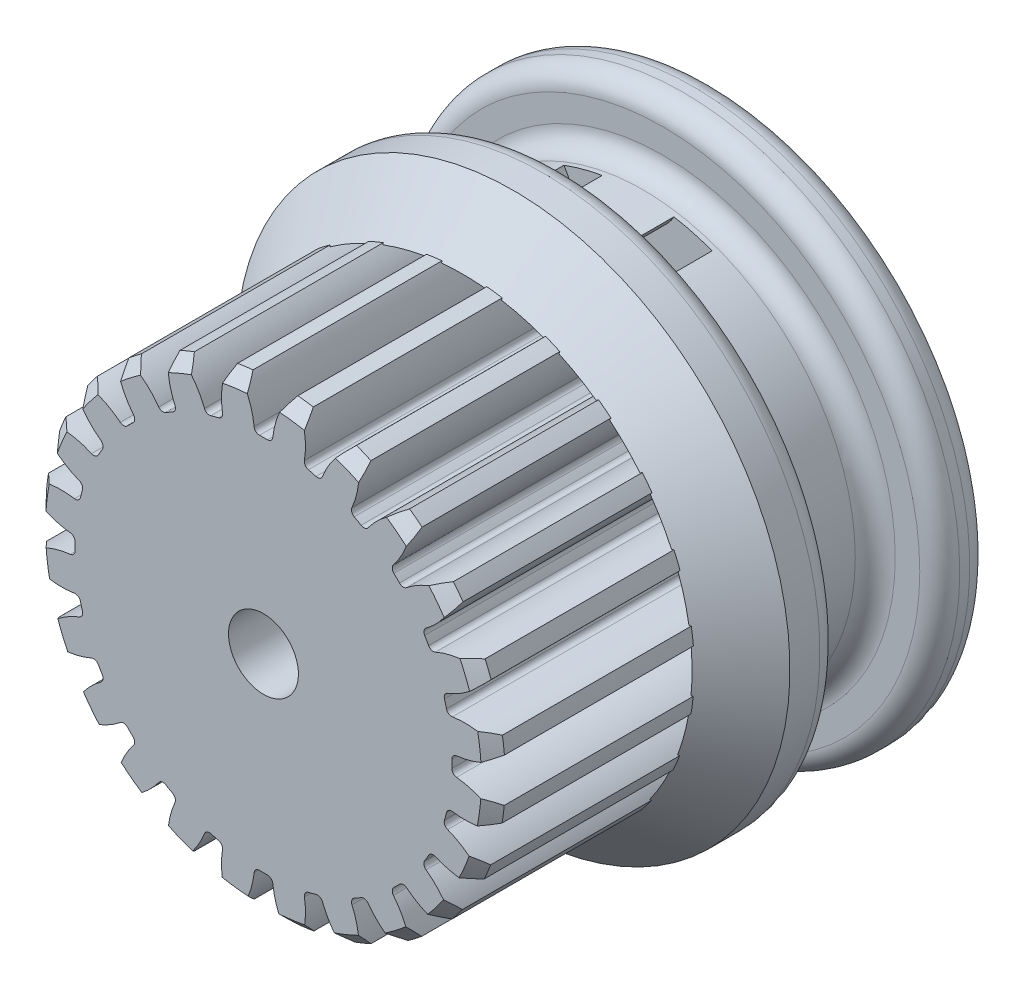
SolidWorks part; units mm, degrees
ref_plane "Plan de face" through (0, 0, 0) normal (0, 0, 1) x (1, 0, 0)
ref_plane "Plan de dessus" through (0, 0, 0) normal (0, 1, 0) x (1, 0, 0)
ref_plane "Plan de droite" through (0, 0, 0) normal (1, 0, 0) x (0, 0, -1)
sketch "Sketch1" plane through (0, 0, 0) normal (0, 0, 1) x (1, 0, 0)
  circle A0 centre (0, 0) radius 21.25 construction
  circle A1 centre (0, 0) radius 23.0208
  dimension "D1" = 42.5
  dimension "D2" = 46.0417
extrude "Boss-Extrude1" add sketch "Sketch1" along normal mid plane 25
sketch "Sketch2" plane through (0, 0, 12.5) normal (0, 0, 1) x (1, 0, 0)
  line L0 (0, 23.0208) -> (0, 0) construction
  line L1 (0, 0) -> (5.9582, 22.2364) construction
  line L2 (0, 0) -> (3.0048, 22.8239) construction
  line L3 (-0.8962, 18.7494) -> (0, 0) construction
  line L4 (-1.3898, 21.2045) -> (1.3898, 21.2045) construction
  line L5 (1.3898, 21.2045) -> (4.1457, 20.8417) construction
  line L6 (-2.0186, 22.9322) -> (0, 17.386) construction
  arc A0 (0.8962, 18.7494) -> (-0.8962, 18.7494) centre (0, 0) ccw
  circle A1 centre (0, 0) radius 19.4792 construction
  circle A2 centre (0, 0) radius 23.0208 construction
  arc A3 (2.2433, 22.9113) -> (0.8962, 18.7494) centre (9.2295, 18.3511) ccw
  arc A4 (-2.2433, 22.9113) -> (-0.8962, 18.7494) centre (-9.2295, 18.3511) cw
  circle A5 centre (0, 0) radius 23.0208 construction
  circle A6 centre (0, 0) radius 21.25 construction
  arc A7 (-2.2433, 22.9113) -> (2.2433, 22.9113) centre (0, 0) cw
  dimension "D1" = 15
  dimension "D2" = 3.5417
  dimension "D3" = 4.25
  dimension "D4" = 20
extrude "Cut-Extrude1" cut sketch "Sketch2" against normal through all
fillet "Fillet1" radius 0.5312 2 edges at (0.8962, 18.7494, 0) (-0.8962, 18.7494, 0)
chamfer "Chamfer1" distance 1.2 1 edges at (0, -23.0208, 12.5)
pattern_circular "CirPattern2" count 24 over 360 about axis through (0, -0.0957, 0) along (0, 0, 1) of "Fillet1", "Cut-Extrude1"
sketch "Sketch4" plane through (0, 0, 0) normal (1, 0, 0) x (0, 0, -1)
  line L2 (12.5, 27.707) -> (17.5, 27.707)
  line L3 (17.5, 27.707) -> (17.5, 21.25)
  line L4 (17.5, 21.25) -> (27.5, 21.25)
  line L5 (27.5, 21.25) -> (27.5, 27.707)
  line L6 (27.5, 27.707) -> (32.5, 27.707)
  line L7 (32.5, 27.707) -> (32.5, 0)
  line L8 (32.5, 0) -> (12.5, 0)
  line L9 (12.5, 0) -> (12.5, 22.9113)
  line L10 (12.5, 22.9113) -> (7.5, 22.9113)
  line L11 (12.5, 22.707) -> (-11.3, 22.707) construction
  line L12 (12.5, 22.9113) -> (-11.3, 22.9113) construction
  line L13 (7.5, 22.9113) -> (12.5, 27.707)
  dimension "D1" = 20
  dimension "D2" = 5
  dimension "D3" = 5
  dimension "D4" = 21.25
  dimension "D5" = 5
  dimension "D6" = 5
  dimension "D7" = 10
revolve "Revolve1" add sketch "Sketch4" angle 360 about L8
fillet "Fillet2" radius 2 5 edges at (-27.707, 0, -17.5) (-21.25, 0, -17.5) (-21.25, 0, -27.5) (-27.707, 0, -27.5) (-27.707, 0, -32.5)
sketch "Sketch5" plane through (0, 0, -32.5) normal (0, 0, -1) x (-1, 0, 0)
  circle A0 centre (0, 0) radius 7
  dimension "D1" = 14
extrude "Boss-Extrude3" add sketch "Sketch5" along normal blind 10
sketch "Sketch6" plane through (0, 0, -42.5) normal (0, 0, -1) x (-1, 0, 0)
  circle A0 centre (0, 0) radius 3.5
  dimension "D1" = 7
extrude "Cut-Extrude2" cut sketch "Sketch6" against normal through all
sketch "Sketch7" plane through (0, 0, 0) normal (1, 0, 0) x (0, 0, -1)
  line L0 (32.5, 0) -> (42.5, 0) construction
  line L1 (32.5, -7) -> (32.5, 7) construction
  line L2 (42.5, -7) -> (42.5, 7) construction
  circle A1 centre (37.5, 0) radius 1.725
  point P8 (0, 0)
  point P9 (37.5, 0)
  dimension "D1" = 3.45
extrude "Cut-Extrude3" cut sketch "Sketch7" against normal blind 10
sketch "Sketch8" plane through (0, 0, 0) normal (0, 0, 1) x (1, 0, 0)
  line L0 (0, 0) -> (0, 27.707) construction
  circle A0 centre (0, 0) radius 21.25 construction
  arc A1 (-7.4207, 19.9122) -> (-3.5898, 20.9446) centre (0, 0) cw
  arc A2 (-7.4207, 19.9122) -> (7.4207, 19.9122) centre (0, 23.5764) ccw
  arc A3 (7.4207, 19.9122) -> (3.5898, 20.9446) centre (0, 0) ccw
  arc A4 (3.5898, 20.9446) -> (-3.5898, 20.9446) centre (0, 22.8372) cw
  point P10 (0, 18.779)
  point P14 (0, 15.3003)
  point P15 (0, 0)
extrude "Cut-Extrude4" cut sketch "Sketch8" against normal blind 5 from offset 20 offset against normal yes
equation "\"Module\" = ( 4.25 / \"Number of teeth\" )"
equation "\"Number of teeth\"= 24"
equation "\"Pressure angle\"= 20"
equation "\"D1@Sketch1\"=\"Module\" * \"Number of teeth\""
equation "\"D2@Sketch1\"=(\"Number of teeth\" + 2) * \"Module\""
equation "\"D2@Sketch2\"=\"Module\"*2"
equation "\"D1@Fillet1\"=0.3*\"Module\""
equation "\"D3@Sketch2\"=\"Module\"*2.4"
equation "\"D4@Sketch2\"=\"Pressure angle\""
equation "\"D1@Sketch2\"=360/\"Number of teeth\""
equation "\"D1@CirPattern2\"=\"Number of teeth\""
